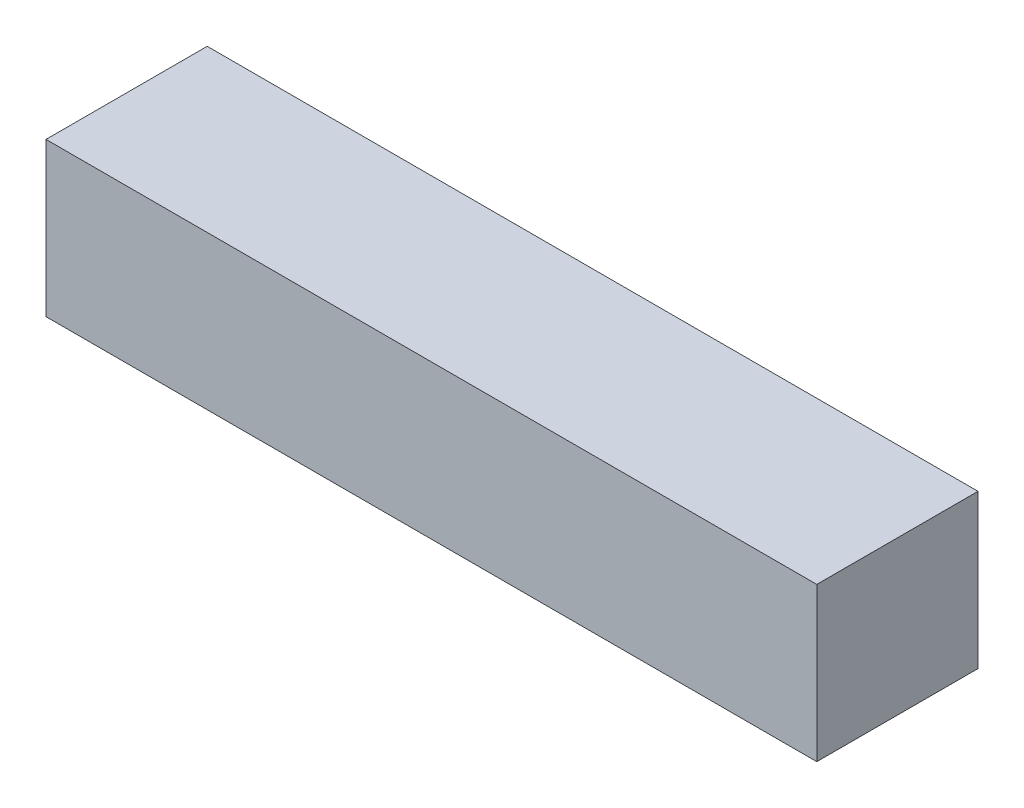
SolidWorks part; units mm, degrees
ref_plane "Front Plane" through (0, 0, 0) normal (0, 0, 1) x (1, 0, 0)
ref_plane "Top Plane" through (0, 0, 0) normal (0, 1, 0) x (1, 0, 0)
ref_plane "Right Plane" through (0, 0, 0) normal (1, 0, 0) x (0, 0, -1)
sketch "Sketch1" plane through (0, 0, 0) normal (0, 1, 0) x (1, 0, 0)
  line L1 (-10.04, -2.1) -> (10.04, -2.1)
  line L2 (-10.04, -2.1) -> (-10.04, 2.1)
  line L3 (-10.04, 2.1) -> (10.04, 2.1)
  line L4 (10.04, -2.1) -> (10.04, 2.1)
  line L5 (-10.04, -2.1) -> (10.04, 2.1) construction
  line L6 (-10.04, 2.1) -> (10.04, -2.1) construction
  point P0 (0, 0)
  dimension "D1" = 20.08
  dimension "D2" = 4.2
extrude "Boss-Extrude1" add sketch "Sketch1" along normal blind 4
